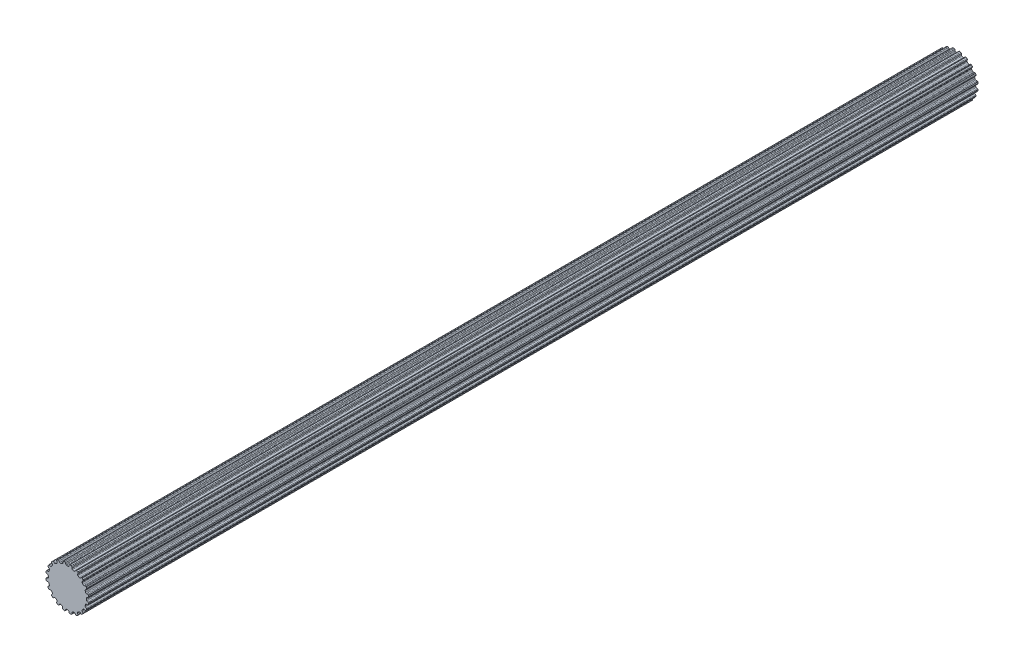
SolidWorks part; units mm, degrees
ref_plane "Front Plane" through (0, 0, 0) normal (0, 0, 1) x (1, 0, 0)
ref_plane "Top Plane" through (0, 0, 0) normal (0, 1, 0) x (1, 0, 0)
ref_plane "Right Plane" through (0, 0, 0) normal (1, 0, 0) x (0, 0, -1)
sketch "Sketch1" plane through (0, 0, 0) normal (0, 0, 1) x (1, 0, 0)
  line L0 (-0.1069, 2.9699) -> (0.1069, 2.9699)
  line L1 (0.3159, 3.2375) -> (0.2537, 3.0575)
  line L2 (-0.2964, 3.2367) -> (-0.2318, 3.0575)
  line L3 (-0.2964, 3.2367) -> (0.3159, 3.2375) construction
  line L4 (0, 3.3252) -> (0, 0) construction
  line L5 (-0.2318, 3.0575) -> (0.2537, 3.0575) construction
  line L6 (-0.4281, 3.3241) -> (0.4281, 3.3263) construction
  line L7 (0.7183, 3.1698) -> (0.7244, 2.9795)
  line L8 (0.816, 2.8576) -> (1.0195, 2.7915)
  line L9 (1.3009, 2.9815) -> (1.1862, 2.8295)
  line L10 (1.6627, 2.7927) -> (1.6097, 2.6099)
  line L11 (1.6591, 2.4655) -> (1.8322, 2.3398)
  line L12 (2.1585, 2.4335) -> (2.0025, 2.3245)
  line L13 (2.4443, 2.1423) -> (2.3374, 1.9847)
  line L14 (2.3398, 1.8322) -> (2.4655, 1.6591)
  line L15 (2.8049, 1.6474) -> (2.6228, 1.5919)
  line L16 (2.9866, 1.2821) -> (2.8363, 1.1653)
  line L17 (2.7915, 1.0195) -> (2.8576, 0.816)
  line L18 (3.1767, 0.7) -> (2.9863, 0.7035)
  line L19 (3.2367, 0.2964) -> (3.0575, 0.2318)
  line L20 (2.9699, 0.1069) -> (2.9699, -0.1069)
  line L21 (3.2375, -0.3159) -> (3.0575, -0.2537)
  line L22 (3.1698, -0.7183) -> (2.9795, -0.7244)
  line L23 (2.8576, -0.816) -> (2.7915, -1.0195)
  line L24 (2.9815, -1.3009) -> (2.8295, -1.1862)
  line L25 (2.7927, -1.6627) -> (2.6099, -1.6097)
  line L26 (2.4655, -1.6591) -> (2.3398, -1.8322)
  line L27 (2.4335, -2.1585) -> (2.3245, -2.0025)
  line L28 (2.1423, -2.4443) -> (1.9847, -2.3374)
  line L29 (1.8322, -2.3398) -> (1.6591, -2.4655)
  line L30 (1.6474, -2.8049) -> (1.5919, -2.6228)
  line L31 (1.2821, -2.9866) -> (1.1653, -2.8363)
  line L32 (1.0195, -2.7915) -> (0.816, -2.8576)
  line L33 (0.7, -3.1767) -> (0.7035, -2.9863)
  line L34 (0.2964, -3.2367) -> (0.2318, -3.0575)
  line L35 (0.1069, -2.9699) -> (-0.1069, -2.9699)
  line L36 (-0.3159, -3.2375) -> (-0.2537, -3.0575)
  line L37 (-0.7183, -3.1698) -> (-0.7244, -2.9795)
  line L38 (-0.816, -2.8576) -> (-1.0195, -2.7915)
  line L39 (-1.3009, -2.9815) -> (-1.1862, -2.8295)
  line L40 (-1.6627, -2.7927) -> (-1.6097, -2.6099)
  line L41 (-1.6591, -2.4655) -> (-1.8322, -2.3398)
  line L42 (-2.1585, -2.4335) -> (-2.0025, -2.3245)
  line L43 (-2.4443, -2.1423) -> (-2.3374, -1.9847)
  line L44 (-2.3398, -1.8322) -> (-2.4655, -1.6591)
  line L45 (-2.8049, -1.6474) -> (-2.6228, -1.5919)
  line L46 (-2.9866, -1.2821) -> (-2.8363, -1.1653)
  line L47 (-2.7915, -1.0195) -> (-2.8576, -0.816)
  line L48 (-3.1767, -0.7) -> (-2.9863, -0.7035)
  line L49 (-3.2367, -0.2964) -> (-3.0575, -0.2318)
  line L50 (-2.9699, -0.1069) -> (-2.9699, 0.1069)
  line L51 (-3.2375, 0.3159) -> (-3.0575, 0.2537)
  line L52 (-3.1698, 0.7183) -> (-2.9795, 0.7244)
  line L53 (-2.8576, 0.816) -> (-2.7915, 1.0195)
  line L54 (-2.9815, 1.3009) -> (-2.8295, 1.1862)
  line L55 (-2.7927, 1.6627) -> (-2.6099, 1.6097)
  line L56 (-2.4655, 1.6591) -> (-2.3398, 1.8322)
  line L57 (-2.4335, 2.1585) -> (-2.3245, 2.0025)
  line L58 (-2.1423, 2.4443) -> (-1.9847, 2.3374)
  line L59 (-1.8322, 2.3398) -> (-1.6591, 2.4655)
  line L60 (-1.6474, 2.8049) -> (-1.5919, 2.6228)
  line L61 (-1.2821, 2.9866) -> (-1.1653, 2.8363)
  line L62 (-1.0195, 2.7915) -> (-0.816, 2.8576)
  line L63 (-0.7, 3.1767) -> (-0.7035, 2.9863)
  line L64 (0.4281, 3.3263) -> (0.62, 3.2938)
  line L65 (1.4351, 3.0312) -> (1.6075, 2.9409)
  line L66 (2.3015, 2.4394) -> (2.4376, 2.3003)
  line L67 (2.9427, 1.6088) -> (3.0291, 1.4344)
  line L68 (3.2958, 0.6207) -> (3.3241, 0.4281)
  line L69 (3.3263, -0.4281) -> (3.2938, -0.62)
  line L70 (3.0312, -1.4351) -> (2.9409, -1.6075)
  line L71 (2.4394, -2.3015) -> (2.3003, -2.4376)
  line L72 (1.6088, -2.9427) -> (1.4344, -3.0291)
  line L73 (0.6207, -3.2958) -> (0.4281, -3.3241)
  line L74 (-0.4281, -3.3263) -> (-0.62, -3.2938)
  line L75 (-1.4351, -3.0312) -> (-1.6075, -2.9409)
  line L76 (-2.3015, -2.4394) -> (-2.4376, -2.3003)
  line L77 (-2.9427, -1.6088) -> (-3.0291, -1.4344)
  line L78 (-3.2958, -0.6207) -> (-3.3241, -0.4281)
  line L79 (-3.3263, 0.4281) -> (-3.2938, 0.62)
  line L80 (-3.0312, 1.4351) -> (-2.9409, 1.6075)
  line L81 (-2.4394, 2.3015) -> (-2.3003, 2.4376)
  line L82 (-1.6088, 2.9427) -> (-1.4344, 3.0291)
  line L83 (-0.6207, 3.2958) -> (-0.4281, 3.3241)
  arc A0 (0.2537, 3.0575) -> (0.1069, 2.9699) centre (0.1283, 3.1009) cw
  arc A1 (-0.2318, 3.0575) -> (-0.1069, 2.9699) centre (-0.1069, 3.1026) ccw
  arc A2 (0.62, 3.2938) -> (0.7183, 3.1698) centre (0.5856, 3.1656) cw
  arc A3 (0.7244, 2.9795) -> (0.816, 2.8576) centre (0.857, 2.9838) ccw
  arc A4 (-0.4281, 3.3241) -> (-0.2964, 3.2367) centre (-0.4213, 3.1916) cw
  arc A5 (0.4281, 3.3263) -> (0.3159, 3.2375) centre (0.4413, 3.1942) ccw
  arc A6 (1.1862, 2.8295) -> (1.0195, 2.7915) centre (1.0802, 2.9095) cw
  arc A7 (1.4351, 3.0312) -> (1.3009, 2.9815) centre (1.4068, 2.9015) ccw
  arc A8 (1.6075, 2.9409) -> (1.6627, 2.7927) centre (1.5352, 2.8297) cw
  arc A9 (1.6097, 2.6099) -> (1.6591, 2.4655) centre (1.7371, 2.5729) ccw
  arc A10 (2.0025, 2.3245) -> (1.8322, 2.3398) centre (1.9264, 2.4332) cw
  arc A11 (2.3015, 2.4394) -> (2.1585, 2.4335) centre (2.2346, 2.3248) ccw
  arc A12 (2.4376, 2.3003) -> (2.4443, 2.1423) centre (2.3345, 2.2168) cw
  arc A13 (2.3374, 1.9847) -> (2.3398, 1.8322) centre (2.4472, 1.9102) ccw
  arc A14 (2.6228, 1.5919) -> (2.4655, 1.6591) centre (2.5841, 1.7189) cw
  arc A15 (2.9427, 1.6088) -> (2.8049, 1.6474) centre (2.8436, 1.5205) ccw
  arc A16 (3.0291, 1.4344) -> (2.9866, 1.2821) centre (2.9052, 1.3869) cw
  arc A17 (2.8363, 1.1653) -> (2.7915, 1.0195) centre (2.9177, 1.0605) ccw
  arc A18 (2.9863, 0.7035) -> (2.8576, 0.816) centre (2.9887, 0.8362) cw
  arc A19 (3.2958, 0.6207) -> (3.1767, 0.7) centre (3.1743, 0.5673) ccw
  arc A20 (3.3241, 0.4281) -> (3.2367, 0.2964) centre (3.1916, 0.4213) cw
  arc A21 (3.0575, 0.2318) -> (2.9699, 0.1069) centre (3.1026, 0.1069) ccw
  arc A22 (3.0575, -0.2537) -> (2.9699, -0.1069) centre (3.1009, -0.1283) cw
  arc A23 (3.3263, -0.4281) -> (3.2375, -0.3159) centre (3.1942, -0.4413) ccw
  arc A24 (3.2938, -0.62) -> (3.1698, -0.7183) centre (3.1656, -0.5856) cw
  arc A25 (2.9795, -0.7244) -> (2.8576, -0.816) centre (2.9838, -0.857) ccw
  arc A26 (2.8295, -1.1862) -> (2.7915, -1.0195) centre (2.9095, -1.0802) cw
  arc A27 (3.0312, -1.4351) -> (2.9815, -1.3009) centre (2.9015, -1.4068) ccw
  arc A28 (2.9409, -1.6075) -> (2.7927, -1.6627) centre (2.8297, -1.5352) cw
  arc A29 (2.6099, -1.6097) -> (2.4655, -1.6591) centre (2.5729, -1.7371) ccw
  arc A30 (2.3245, -2.0025) -> (2.3398, -1.8322) centre (2.4332, -1.9264) cw
  arc A31 (2.4394, -2.3015) -> (2.4335, -2.1585) centre (2.3248, -2.2346) ccw
  arc A32 (2.3003, -2.4376) -> (2.1423, -2.4443) centre (2.2168, -2.3345) cw
  arc A33 (1.9847, -2.3374) -> (1.8322, -2.3398) centre (1.9102, -2.4472) ccw
  arc A34 (1.5919, -2.6228) -> (1.6591, -2.4655) centre (1.7189, -2.5841) cw
  arc A35 (1.6088, -2.9427) -> (1.6474, -2.8049) centre (1.5205, -2.8436) ccw
  arc A36 (1.4344, -3.0291) -> (1.2821, -2.9866) centre (1.3869, -2.9052) cw
  arc A37 (1.1653, -2.8363) -> (1.0195, -2.7915) centre (1.0605, -2.9177) ccw
  arc A38 (0.7035, -2.9863) -> (0.816, -2.8576) centre (0.8362, -2.9887) cw
  arc A39 (0.6207, -3.2958) -> (0.7, -3.1767) centre (0.5673, -3.1743) ccw
  arc A40 (0.4281, -3.3241) -> (0.2964, -3.2367) centre (0.4213, -3.1916) cw
  arc A41 (0.2318, -3.0575) -> (0.1069, -2.9699) centre (0.1069, -3.1026) ccw
  arc A42 (-0.2537, -3.0575) -> (-0.1069, -2.9699) centre (-0.1283, -3.1009) cw
  arc A43 (-0.4281, -3.3263) -> (-0.3159, -3.2375) centre (-0.4413, -3.1942) ccw
  arc A44 (-0.62, -3.2938) -> (-0.7183, -3.1698) centre (-0.5856, -3.1656) cw
  arc A45 (-0.7244, -2.9795) -> (-0.816, -2.8576) centre (-0.857, -2.9838) ccw
  arc A46 (-1.1862, -2.8295) -> (-1.0195, -2.7915) centre (-1.0802, -2.9095) cw
  arc A47 (-1.4351, -3.0312) -> (-1.3009, -2.9815) centre (-1.4068, -2.9015) ccw
  arc A48 (-1.6075, -2.9409) -> (-1.6627, -2.7927) centre (-1.5352, -2.8297) cw
  arc A49 (-1.6097, -2.6099) -> (-1.6591, -2.4655) centre (-1.7371, -2.5729) ccw
  arc A50 (-2.0025, -2.3245) -> (-1.8322, -2.3398) centre (-1.9264, -2.4332) cw
  arc A51 (-2.3015, -2.4394) -> (-2.1585, -2.4335) centre (-2.2346, -2.3248) ccw
  arc A52 (-2.4376, -2.3003) -> (-2.4443, -2.1423) centre (-2.3345, -2.2168) cw
  arc A53 (-2.3374, -1.9847) -> (-2.3398, -1.8322) centre (-2.4472, -1.9102) ccw
  arc A54 (-2.6228, -1.5919) -> (-2.4655, -1.6591) centre (-2.5841, -1.7189) cw
  arc A55 (-2.9427, -1.6088) -> (-2.8049, -1.6474) centre (-2.8436, -1.5205) ccw
  arc A56 (-3.0291, -1.4344) -> (-2.9866, -1.2821) centre (-2.9052, -1.3869) cw
  arc A57 (-2.8363, -1.1653) -> (-2.7915, -1.0195) centre (-2.9177, -1.0605) ccw
  arc A58 (-2.9863, -0.7035) -> (-2.8576, -0.816) centre (-2.9887, -0.8362) cw
  arc A59 (-3.2958, -0.6207) -> (-3.1767, -0.7) centre (-3.1743, -0.5673) ccw
  arc A60 (-3.3241, -0.4281) -> (-3.2367, -0.2964) centre (-3.1916, -0.4213) cw
  arc A61 (-3.0575, -0.2318) -> (-2.9699, -0.1069) centre (-3.1026, -0.1069) ccw
  arc A62 (-3.0575, 0.2537) -> (-2.9699, 0.1069) centre (-3.1009, 0.1283) cw
  arc A63 (-3.3263, 0.4281) -> (-3.2375, 0.3159) centre (-3.1942, 0.4413) ccw
  arc A64 (-3.2938, 0.62) -> (-3.1698, 0.7183) centre (-3.1656, 0.5856) cw
  arc A65 (-2.9795, 0.7244) -> (-2.8576, 0.816) centre (-2.9838, 0.857) ccw
  arc A66 (-2.8295, 1.1862) -> (-2.7915, 1.0195) centre (-2.9095, 1.0802) cw
  arc A67 (-3.0312, 1.4351) -> (-2.9815, 1.3009) centre (-2.9015, 1.4068) ccw
  arc A68 (-2.9409, 1.6075) -> (-2.7927, 1.6627) centre (-2.8297, 1.5352) cw
  arc A69 (-2.6099, 1.6097) -> (-2.4655, 1.6591) centre (-2.5729, 1.7371) ccw
  arc A70 (-2.3245, 2.0025) -> (-2.3398, 1.8322) centre (-2.4332, 1.9264) cw
  arc A71 (-2.4394, 2.3015) -> (-2.4335, 2.1585) centre (-2.3248, 2.2346) ccw
  arc A72 (-2.3003, 2.4376) -> (-2.1423, 2.4443) centre (-2.2168, 2.3345) cw
  arc A73 (-1.9847, 2.3374) -> (-1.8322, 2.3398) centre (-1.9102, 2.4472) ccw
  arc A74 (-1.5919, 2.6228) -> (-1.6591, 2.4655) centre (-1.7189, 2.5841) cw
  arc A75 (-1.6088, 2.9427) -> (-1.6474, 2.8049) centre (-1.5205, 2.8436) ccw
  arc A76 (-1.4344, 3.0291) -> (-1.2821, 2.9866) centre (-1.3869, 2.9052) cw
  arc A77 (-1.1653, 2.8363) -> (-1.0195, 2.7915) centre (-1.0605, 2.9177) ccw
  arc A78 (-0.7035, 2.9863) -> (-0.816, 2.8576) centre (-0.8362, 2.9887) cw
  arc A79 (-0.6207, 3.2958) -> (-0.7, 3.1767) centre (-0.5673, 3.1743) ccw
  point P14 (0, 2.9699)
  point P247 (0, 0)
  dimension "D4" = 0.1327
  dimension "D8" = 20
  dimension "D1" = 2.9699
  dimension "D2" = 0.2139
  dimension "D3" = 0.1904
  dimension "D5" = 0.0877
  dimension "D6" = 0.4855
  dimension "D7" = 0.8563
extrude "Boss-Extrude1" add sketch "Sketch1" along normal mid plane 138.938
sketch "Sketch2" plane through (0, 0, 69.469) normal (0, 0, 1) x (1, 0, 0)
  circle A0 centre (0, 0) radius 3.3516 construction
sketch "Sketch3" plane through (0, 0, -69.469) normal (0, 0, -1) x (-1, 0, 0)
  circle A0 centre (0, 0) radius 3.3516 construction
  circle A1 centre (0, 0) radius 3.3516 construction
